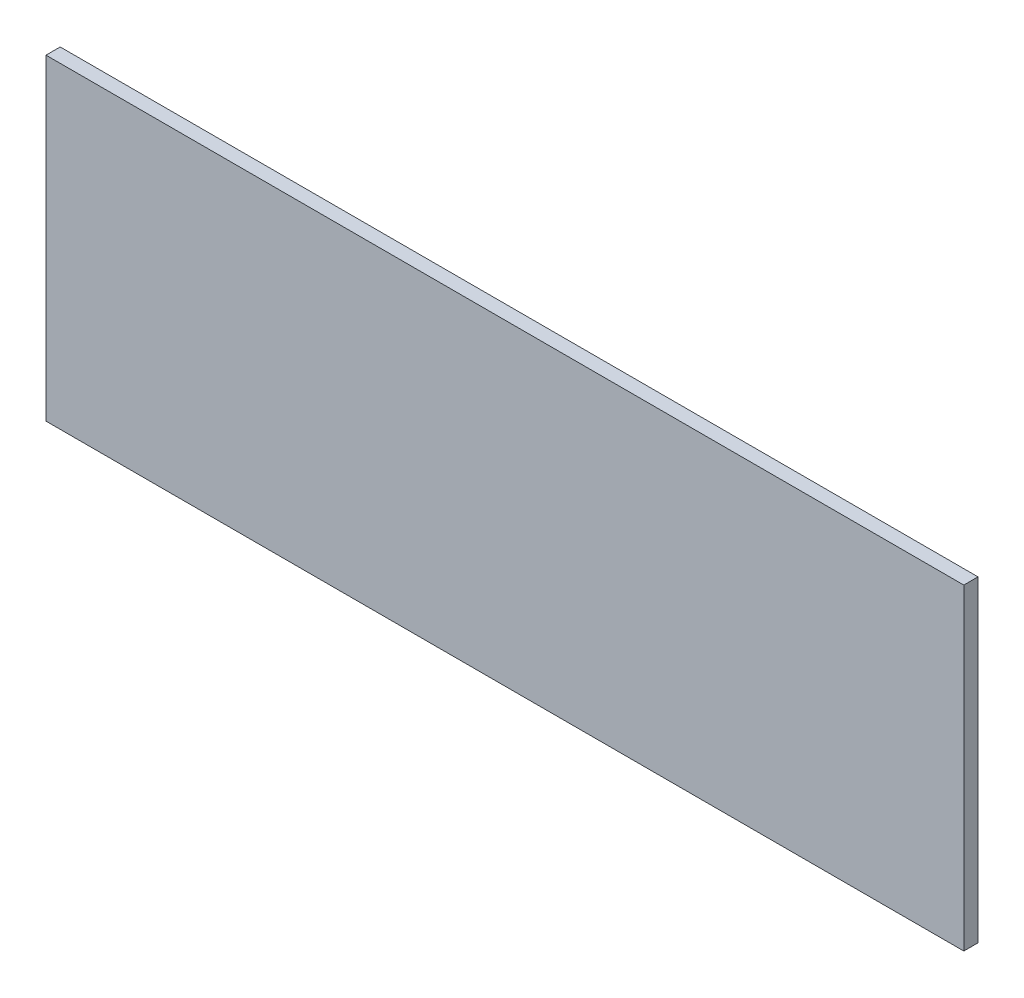
SolidWorks part; units mm, degrees
ref_plane "Front Plane" through (0, 0, 0) normal (0, 0, 1) x (1, 0, 0)
ref_plane "Top Plane" through (0, 0, 0) normal (0, 1, 0) x (1, 0, 0)
ref_plane "Right Plane" through (0, 0, 0) normal (1, 0, 0) x (0, 0, -1)
sketch "Sketch1" plane through (0, 0, 0) normal (0, 0, 1) x (1, 0, 0)
  line L1 (0, 0) -> (194, 0)
  line L2 (0, 0) -> (0, 67)
  line L3 (0, 67) -> (194, 67)
  line L4 (194, 0) -> (194, 67)
  dimension "D1" = 194
  dimension "D2" = 67
extrude "Profile" add sketch "Sketch1" along normal blind 3
equation "\"Profile_Depth\"= 3mm"
equation "\"D1@Profile\" = \"Profile_Depth\""
equation "\"Profile_Sketch_1\"= 194mm"
equation "\"D1@Sketch1\" = \"Profile_Sketch_1\""
equation "\"Profile_Sketch_2\"= 67mm"
equation "\"D2@Sketch1\" = \"Profile_Sketch_2\""
equation "\"EnvelopeWidth\"= 194mm"
equation "\"EnvelopeHeight\"= 67mm"
